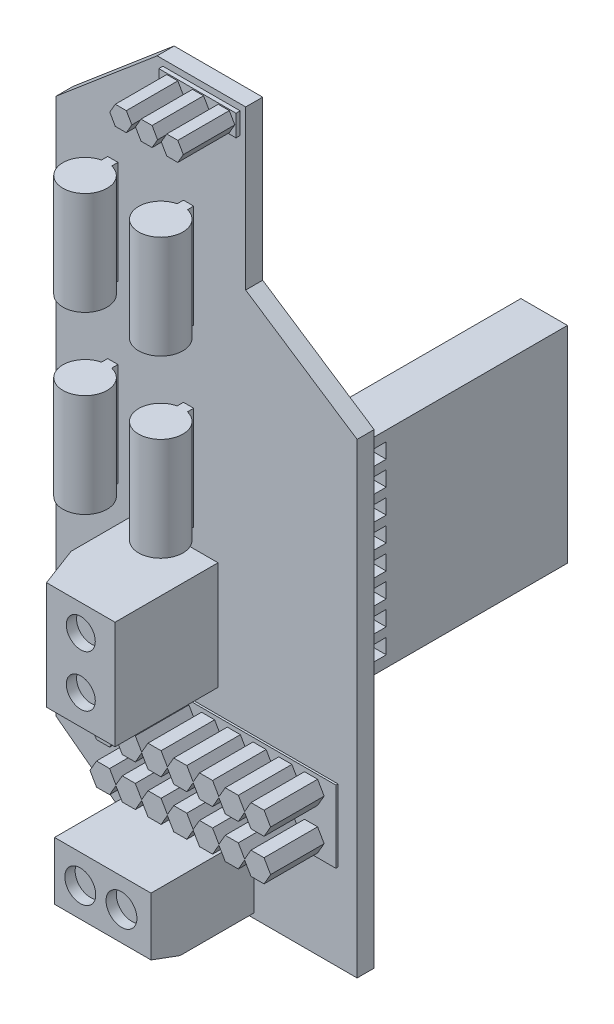
SolidWorks part; units mm, degrees
material "CA"
ref_plane "Plan de face" through (0, 0, 0) normal (0, 0, 1) x (1, 0, 0)
ref_plane "Plan de dessus" through (0, 0, 0) normal (0, 1, 0) x (1, 0, 0)
ref_plane "Plan de droite" through (0, 0, 0) normal (1, 0, 0) x (0, 0, -1)
sketch "Esquisse1" plane through (0, 0, 0) normal (0, 0, 1) x (1, 0, 0)
  line L0 (-11.323, 33.4799) -> (-2.723, 33.4799)
  line L1 (-2.723, 33.4799) -> (-2.723, 18.0799)
  line L2 (-2.723, 18.0799) -> (8.097, 10.9292)
  line L3 (8.097, 10.9292) -> (8.097, -34.3701)
  line L4 (8.097, -34.3701) -> (-11.323, -34.3701)
  line L5 (-11.323, -34.3701) -> (-21.143, -26.9701)
  line L6 (-21.143, -26.9701) -> (-21.143, 25.1718)
  line L7 (-21.143, 25.1718) -> (-11.323, 33.4799)
  dimension "D1" = 67.85
  dimension "D2" = 29.24
  dimension "D3" = 8.6
  dimension "D4" = 18.42
  dimension "D5" = 15.4
  dimension "D6" = 7.4
extrude "Boss.-Extru.1" add sketch "Esquisse1" along normal blind 1.65
sketch "Esquisse2" plane through (0, 0, 1.65) normal (0, 0, 1) x (1, 0, 0)
  line L0 (-15.6256, 15.1125) -> (-15.6256, -11.4034) construction
  line L1 (-10.7643, 32.8838) -> (-3.2638, 32.8838)
  line L2 (-10.7643, 32.8838) -> (-10.7643, 30.8058)
  line L3 (-10.7643, 30.8058) -> (-3.2638, 30.8058)
  line L4 (-3.2638, 32.8838) -> (-3.2638, 30.8058)
  line L5 (-10.7643, 32.8838) -> (-3.2638, 30.8058) construction
  line L6 (-10.7643, 30.8058) -> (-3.2638, 32.8838) construction
  line L7 (-8.2696, 18.1286) -> (-8.2696, -8.3873) construction
  line L9 (-17.8756, 22.6159) -> (-13.3756, 22.6159)
  line L10 (-17.8756, 22.6159) -> (-17.8756, 12.6159)
  line L11 (-17.8756, 12.6159) -> (-13.3756, 12.6159)
  line L12 (-13.3756, 22.6159) -> (-13.3756, 12.6159)
  line L13 (-17.8756, 22.6159) -> (-13.3756, 12.6159) construction
  line L14 (-17.8756, 12.6159) -> (-13.3756, 22.6159) construction
  line L15 (-10.5196, 22.6159) -> (-6.0196, 22.6159)
  line L16 (-10.5196, 22.6159) -> (-10.5196, 12.6159)
  line L17 (-10.5196, 12.6159) -> (-6.0196, 12.6159)
  line L18 (-6.0196, 22.6159) -> (-6.0196, 12.6159)
  line L19 (-10.5196, 22.6159) -> (-6.0196, 12.6159) construction
  line L20 (-10.5196, 12.6159) -> (-6.0196, 22.6159) construction
  line L21 (-17.8756, 5.6159) -> (-13.3756, 5.6159)
  line L22 (-17.8756, 5.6159) -> (-17.8756, -4.3841)
  line L23 (-17.8756, -4.3841) -> (-13.3756, -4.3841)
  line L24 (-13.3756, 5.6159) -> (-13.3756, -4.3841)
  line L25 (-17.8756, 5.6159) -> (-13.3756, -4.3841) construction
  line L26 (-17.8756, -4.3841) -> (-13.3756, 5.6159) construction
  line L27 (-10.5196, 5.6159) -> (-6.0196, 5.6159)
  line L28 (-10.5196, 5.6159) -> (-10.5196, -4.3841)
  line L29 (-10.5196, -4.3841) -> (-6.0196, -4.3841)
  line L30 (-6.0196, 5.6159) -> (-6.0196, -4.3841)
  line L31 (-10.5196, 5.6159) -> (-6.0196, -4.3841) construction
  line L32 (-10.5196, -4.3841) -> (-6.0196, 5.6159) construction
  line L33 (-12.7638, -18.9755) -> (6.2362, -18.9755)
  line L34 (-12.7638, -18.9755) -> (-12.7638, -25.9755)
  line L35 (-12.7638, -25.9755) -> (6.2362, -25.9755)
  line L36 (6.2362, -18.9755) -> (6.2362, -25.9755)
  line L37 (-12.7638, -18.9755) -> (6.2362, -25.9755) construction
  line L38 (-12.7638, -25.9755) -> (6.2362, -18.9755) construction
  point P0 (-7.0141, 31.8448)
  point P9 (-15.6256, 17.6159)
  point P14 (-8.2696, 17.6159)
  point P19 (-15.6256, 0.6159)
  point P24 (-8.2696, 0.6159)
  point P30 (-3.2638, -22.4755)
  dimension "D1" = 4.5
  dimension "D2" = 10
  dimension "D3" = 7
  dimension "D4" = 7
  dimension "D5" = 19
  dimension "D6" = 7
extrude "Boss.-Extru.2" add sketch "Esquisse2" along normal blind 5.4
sketch "Esquisse3" plane through (0, 0, 1.65) normal (0, 0, 1) x (1, 0, 0)
  line L5 (-11.2863, -33.9075) -> (-1.9184, -33.9075)
  line L6 (-11.2863, -33.9075) -> (-11.2863, -27.2388)
  line L7 (-11.2863, -27.2388) -> (-1.9184, -27.2388)
  line L8 (-1.9184, -33.9075) -> (-1.9184, -27.2388)
  line L9 (-11.2863, -33.9075) -> (-1.9184, -27.2388) construction
  line L10 (-11.2863, -27.2388) -> (-1.9184, -33.9075) construction
  line L11 (-5.4116, -16.6801) -> (-13.5092, -16.6801)
  line L12 (-5.4116, -16.6801) -> (-5.4116, -6.2008)
  line L13 (-5.4116, -6.2008) -> (-13.5092, -6.2008)
  line L14 (-13.5092, -16.6801) -> (-13.5092, -6.2008)
  line L15 (-5.4116, -16.6801) -> (-13.5092, -6.2008) construction
  line L16 (-5.4116, -6.2008) -> (-13.5092, -16.6801) construction
  point P0 (-6.6024, -30.5731)
  point P5 (-9.4604, -11.4404)
extrude "Boss.-Extru.3" add sketch "Esquisse3" along normal blind 10
sketch "Esquisse4" plane through (0, 0, 0) normal (0, 0, -1) x (-1, 0, 0)
  line L0 (-8.097, -34.3701) -> (-8.097, 10.9292) construction
  line L1 (-5.277, 7.4799) -> (-0.757, 7.4799)
  line L2 (-5.277, 7.4799) -> (-5.277, -12.5201)
  line L3 (-5.277, -12.5201) -> (-0.757, -12.5201)
  line L4 (-0.757, 7.4799) -> (-0.757, -12.5201)
  line L5 (-5.277, 7.4799) -> (-0.757, -12.5201) construction
  line L6 (-5.277, -12.5201) -> (-0.757, 7.4799) construction
  line L7 (2.723, 33.4799) -> (11.323, 33.4799) construction
  point P0 (-3.017, -2.5201)
  dimension "D1" = 7.34
  dimension "D2" = 4.52
  dimension "D3" = 20
  dimension "D4" = 26
extrude "Boss.-Extru.4" add sketch "Esquisse4" along normal blind 21.6
sketch "Esquisse5" plane through (0, -4.3841, 0) normal (0, -1, 0) x (1, 0, 0)
  line L0 (-13.3756, 7.05) -> (-17.8756, 1.65) construction
  line L10 (-17.8756, 1.65) -> (-13.3756, 1.65) construction
  line L11 (-16.1256, 2.75) -> (-15.1256, 2.75)
  line L12 (-16.1256, 2.75) -> (-16.1256, 1.65)
  line L13 (-16.1256, 1.65) -> (-15.1256, 1.65)
  line L14 (-15.1256, 2.75) -> (-15.1256, 1.65)
  line L15 (-16.1256, 2.75) -> (-15.1256, 1.65) construction
  line L16 (-16.1256, 1.65) -> (-15.1256, 2.75) construction
  circle A2 centre (-15.6256, 4.35) radius 2.15
  point P7 (-15.6256, 2.2)
  line M2 (-17.8756, 1.65) -> (-13.3756, 1.65)
  line M3 (-13.3756, 1.65) -> (-13.3756, 7.05)
  line M4 (-13.3756, 7.05) -> (-17.8756, 7.05)
  line M5 (-17.8756, 7.05) -> (-17.8756, 1.65)
  dimension "D1" = 4.3
  dimension "D2" = 1
extrude "Enlèv. mat.-Extru.3" cut sketch "Esquisse5" against normal blind 27 contours A2 L14 L12 M2 M3 M4 M5
sketch "Esquisse6" plane through (0, 22.6159, 0) normal (0, 1, 0) x (1, 0, 0)
  line L0 (-6.0196, -7.05) -> (-10.5196, -1.65) construction
  line L1 (-6.0196, -1.65) -> (-10.5196, -1.65) construction
  line L2 (-7.7696, -2.75) -> (-8.7696, -2.75)
  line L3 (-7.7696, -2.75) -> (-7.7696, -1.65)
  line L4 (-7.7696, -1.65) -> (-8.7696, -1.65)
  line L5 (-8.7696, -2.75) -> (-8.7696, -1.65)
  line L6 (-7.7696, -2.75) -> (-8.7696, -1.65) construction
  line L7 (-7.7696, -1.65) -> (-8.7696, -2.75) construction
  circle A0 centre (-8.2696, -4.35) radius 2.15
  point P6 (-8.2696, -2.2)
  line M2 (-6.0196, -1.65) -> (-10.5196, -1.65)
  line M3 (-10.5196, -1.65) -> (-10.5196, -7.05)
  line M4 (-10.5196, -7.05) -> (-6.0196, -7.05)
  line M5 (-6.0196, -7.05) -> (-6.0196, -1.65)
  dimension "D1" = 4.3
  dimension "D2" = 1
extrude "Enlèv. mat.-Extru.4" cut sketch "Esquisse6" against normal blind 27 contours A0 L5 L3 M2 M3 M4 M5
sketch "Esquisse8" plane through (0, 0, 7.05) normal (0, 0, 1) x (1, 0, 0)
  line L0 (6.2362, -18.9755) -> (-12.7638, -18.9755) construction
  line L1 (-10.5397, -19.3723) -> (-11.8109, -19.3723)
  line L2 (-11.8109, -19.3723) -> (-12.4465, -20.4732)
  line L3 (-12.4465, -20.4732) -> (-11.8109, -21.5742)
  line L4 (-11.8109, -21.5742) -> (-10.5397, -21.5742)
  line L5 (-10.5397, -21.5742) -> (-9.9041, -20.4732)
  line L6 (-9.9041, -20.4732) -> (-10.5397, -19.3723)
  line L7 (-8.0397, -19.3723) -> (-9.3109, -19.3723)
  line L8 (-9.3109, -19.3723) -> (-9.9465, -20.4732)
  line L9 (-9.9465, -20.4732) -> (-9.3109, -21.5742)
  line L10 (-9.3109, -21.5742) -> (-8.0397, -21.5742)
  line L11 (-8.0397, -21.5742) -> (-7.4041, -20.4732)
  line L12 (-7.4041, -20.4732) -> (-8.0397, -19.3723)
  line L13 (-5.5397, -19.3723) -> (-6.8109, -19.3723)
  line L14 (-6.8109, -19.3723) -> (-7.4465, -20.4732)
  line L15 (-7.4465, -20.4732) -> (-6.8109, -21.5742)
  line L16 (-6.8109, -21.5742) -> (-5.5397, -21.5742)
  line L17 (-5.5397, -21.5742) -> (-4.9041, -20.4732)
  line L18 (-4.9041, -20.4732) -> (-5.5397, -19.3723)
  line L19 (-3.0397, -19.3723) -> (-4.3109, -19.3723)
  line L20 (-4.3109, -19.3723) -> (-4.9465, -20.4732)
  line L21 (-4.9465, -20.4732) -> (-4.3109, -21.5742)
  line L22 (-4.3109, -21.5742) -> (-3.0397, -21.5742)
  line L23 (-3.0397, -21.5742) -> (-2.4041, -20.4732)
  line L24 (-2.4041, -20.4732) -> (-3.0397, -19.3723)
  line L25 (-0.5397, -19.3723) -> (-1.8109, -19.3723)
  line L26 (-1.8109, -19.3723) -> (-2.4465, -20.4732)
  line L27 (-2.4465, -20.4732) -> (-1.8109, -21.5742)
  line L28 (-1.8109, -21.5742) -> (-0.5397, -21.5742)
  line L29 (-0.5397, -21.5742) -> (0.0959, -20.4732)
  line L30 (0.0959, -20.4732) -> (-0.5397, -19.3723)
  line L31 (1.9603, -19.3723) -> (0.6891, -19.3723)
  line L32 (0.6891, -19.3723) -> (0.0535, -20.4732)
  line L33 (0.0535, -20.4732) -> (0.6891, -21.5742)
  line L34 (0.6891, -21.5742) -> (1.9603, -21.5742)
  line L35 (1.9603, -21.5742) -> (2.5959, -20.4732)
  line L36 (2.5959, -20.4732) -> (1.9603, -19.3723)
  line L37 (4.4603, -19.3723) -> (3.1891, -19.3723)
  line L38 (3.1891, -19.3723) -> (2.5535, -20.4732)
  line L39 (2.5535, -20.4732) -> (3.1891, -21.5742)
  line L40 (3.1891, -21.5742) -> (4.4603, -21.5742)
  line L41 (4.4603, -21.5742) -> (5.0959, -20.4732)
  line L42 (5.0959, -20.4732) -> (4.4603, -19.3723)
  line L43 (-8.0397, -23.3723) -> (-9.3109, -23.3723)
  line L44 (-9.3109, -23.3723) -> (-9.9465, -24.4732)
  line L45 (-9.9465, -24.4732) -> (-9.3109, -25.5742)
  line L46 (-9.3109, -25.5742) -> (-8.0397, -25.5742)
  line L47 (-8.0397, -25.5742) -> (-7.4041, -24.4732)
  line L48 (-7.4041, -24.4732) -> (-8.0397, -23.3723)
  line L49 (-5.5397, -23.3723) -> (-6.8109, -23.3723)
  line L50 (-6.8109, -23.3723) -> (-7.4465, -24.4732)
  line L51 (-7.4465, -24.4732) -> (-6.8109, -25.5742)
  line L52 (-6.8109, -25.5742) -> (-5.5397, -25.5742)
  line L53 (-5.5397, -25.5742) -> (-4.9041, -24.4732)
  line L54 (-4.9041, -24.4732) -> (-5.5397, -23.3723)
  line L55 (-3.0397, -23.3723) -> (-4.3109, -23.3723)
  line L56 (-4.3109, -23.3723) -> (-4.9465, -24.4732)
  line L57 (-4.9465, -24.4732) -> (-4.3109, -25.5742)
  line L58 (-4.3109, -25.5742) -> (-3.0397, -25.5742)
  line L59 (-3.0397, -25.5742) -> (-2.4041, -24.4732)
  line L60 (-2.4041, -24.4732) -> (-3.0397, -23.3723)
  line L61 (-0.5397, -23.3723) -> (-1.8109, -23.3723)
  line L62 (-1.8109, -23.3723) -> (-2.4465, -24.4732)
  line L63 (-2.4465, -24.4732) -> (-1.8109, -25.5742)
  line L64 (-1.8109, -25.5742) -> (-0.5397, -25.5742)
  line L65 (-0.5397, -25.5742) -> (0.0959, -24.4732)
  line L66 (0.0959, -24.4732) -> (-0.5397, -23.3723)
  line L67 (1.9603, -23.3723) -> (0.6891, -23.3723)
  line L68 (0.6891, -23.3723) -> (0.0535, -24.4732)
  line L69 (0.0535, -24.4732) -> (0.6891, -25.5742)
  line L70 (0.6891, -25.5742) -> (1.9603, -25.5742)
  line L71 (1.9603, -25.5742) -> (2.5959, -24.4732)
  line L72 (2.5959, -24.4732) -> (1.9603, -23.3723)
  line L73 (4.4603, -23.3723) -> (3.1891, -23.3723)
  line L74 (3.1891, -23.3723) -> (2.5535, -24.4732)
  line L75 (2.5535, -24.4732) -> (3.1891, -25.5742)
  line L76 (3.1891, -25.5742) -> (4.4603, -25.5742)
  line L77 (4.4603, -25.5742) -> (5.0959, -24.4732)
  line L78 (5.0959, -24.4732) -> (4.4603, -23.3723)
  line L79 (-10.5397, -23.3723) -> (-11.8109, -23.3723)
  line L80 (-11.8109, -23.3723) -> (-12.4465, -24.4732)
  line L81 (-12.4465, -24.4732) -> (-11.8109, -25.5742)
  line L82 (-11.8109, -25.5742) -> (-10.5397, -25.5742)
  line L83 (-10.5397, -25.5742) -> (-9.9041, -24.4732)
  line L84 (-9.9041, -24.4732) -> (-10.5397, -23.3723)
  circle A0 centre (-11.1753, -20.4732) radius 1.1009 construction
  circle A1 centre (-8.6753, -20.4732) radius 1.1009 construction
  circle A2 centre (-6.1753, -20.4732) radius 1.1009 construction
  circle A3 centre (-3.6753, -20.4732) radius 1.1009 construction
  circle A4 centre (-1.1753, -20.4732) radius 1.1009 construction
  circle A5 centre (1.3247, -20.4732) radius 1.1009 construction
  circle A6 centre (3.8247, -20.4732) radius 1.1009 construction
  circle A7 centre (-8.6753, -24.4732) radius 1.1009 construction
  circle A8 centre (-6.1753, -24.4732) radius 1.1009 construction
  circle A9 centre (-3.6753, -24.4732) radius 1.1009 construction
  circle A10 centre (-1.1753, -24.4732) radius 1.1009 construction
  circle A11 centre (1.3247, -24.4732) radius 1.1009 construction
  circle A12 centre (3.8247, -24.4732) radius 1.1009 construction
  circle A13 centre (-11.1753, -24.4732) radius 1.1009 construction
  line M2 (6.2362, -25.9755) -> (6.2362, -18.9755)
  line M3 (6.2362, -18.9755) -> (-12.7638, -18.9755)
  line M4 (-12.7638, -18.9755) -> (-12.7638, -25.9755)
  line M5 (-12.7638, -25.9755) -> (6.2362, -25.9755)
  dimension "D1" = 7
  dimension "D2" = 2
extrude "Enlèv. mat.-Extru.10" cut sketch "Esquisse8" against normal blind 5.2 contours L84 L44 L43 L48 L50 L49 L54 L56 L55 L60 L62 L61 L66 L68 L67 L72 L74 L73 L78 L77 L76 L75 L71 L70 L69 L65 L64 L63 L59 L58 L57 L53 L52 L51 L47 L46 L45 L83 L82 L81 L80 L79 L42 L41 L40 M5 M2 M3 M4
sketch "Esquisse9" plane through (-13.5092, 0, 0) normal (-1, 0, 0) x (0, 0, 1)
  line L0 (1.65, -9.2008) -> (11.65, -9.2008) construction
  line L1 (1.65, -6.2008) -> (1.65, -16.6801) construction
  line L2 (11.65, -6.2008) -> (11.65, -16.6801) construction
  line L3 (1.65, -13.2008) -> (11.65, -13.2008) construction
  line L4 (11.65, -6.2008) -> (1.65, -6.2008) construction
  line L6 (2.4565, -7.4967) -> (7.1773, -7.4967)
  line L7 (2.4565, -7.4967) -> (2.4565, -10.9048)
  line L8 (2.4565, -10.9048) -> (7.1773, -10.9048)
  line L9 (7.1773, -7.4967) -> (7.1773, -10.9048)
  line L10 (2.4565, -7.4967) -> (7.1773, -10.9048) construction
  line L11 (2.4565, -10.9048) -> (7.1773, -7.4967) construction
  line L12 (2.4565, -11.4967) -> (7.1773, -11.4967)
  line L13 (2.4565, -11.4967) -> (2.4565, -14.9048)
  line L14 (2.4565, -14.9048) -> (7.1773, -14.9048)
  line L15 (7.1773, -11.4967) -> (7.1773, -14.9048)
  line L16 (2.4565, -11.4967) -> (7.1773, -14.9048) construction
  line L17 (2.4565, -14.9048) -> (7.1773, -11.4967) construction
  point P10 (4.8169, -9.2008)
  point P15 (4.8169, -13.2008)
  dimension "D1" = 4
  dimension "D2" = 3
extrude "Enlèv. mat.-Extru.11" cut sketch "Esquisse9" against normal blind 5.2
sketch "Esquisse10" plane through (0, -16.6801, 0) normal (0, -1, 0) x (1, 0, 0)
  line L0 (-13.5092, 11.65) -> (-13.5092, 7.8248)
  line L1 (-13.5092, 11.65) -> (-13.5092, 1.65) construction
  line L2 (-13.5092, 7.8248) -> (-12.0645, 11.65)
  line L3 (-13.5092, 11.65) -> (-5.4116, 11.65) construction
  line L4 (-12.0645, 11.65) -> (-13.5092, 11.65)
extrude "Enlèv. mat.-Extru.12" cut sketch "Esquisse10" against normal up to surface (10.4793 mm away) up to face at (-9.4604, -6.2008, 6.65)
sketch "Esquisse11" plane through (0, 0, 11.65) normal (0, 0, 1) x (1, 0, 0)
  line L0 (-8.738, -6.2008) -> (-8.738, -16.6801) construction
  line L1 (-5.4116, -6.2008) -> (-12.0645, -6.2008) construction
  line L2 (-12.0645, -16.6801) -> (-5.4116, -16.6801) construction
  circle A0 centre (-8.738, -8.7833) radius 1.4089
  circle A1 centre (-8.738, -13.7833) radius 1.4089
  dimension "D1" = 5
extrude "Enlèv. mat.-Extru.13" cut sketch "Esquisse11" against normal blind 1
sketch "Esquisse12" plane through (5.277, 0, 0) normal (1, 0, 0) x (0, 0, -1)
  line L0 (0, 33.4799) -> (0, 25.1718) construction
  line L1 (0, -11.4237) -> (4, -11.4237)
  line L2 (0, -11.4237) -> (0, -9.9502)
  line L3 (0, -9.9502) -> (4, -9.9502)
  line L4 (4, -11.4237) -> (4, -9.9502)
  line L5 (0, -11.4237) -> (4, -9.9502) construction
  line L6 (0, -9.9502) -> (4, -11.4237) construction
  point P0 (2, -10.6869)
  dimension "D1" = 4
extrude "Enlèv. mat.-Extru.14" cut sketch "Esquisse12" against normal blind 5
pattern_linear "Répétition linéaire2" count 8 spacing 2.35 along (0, 1, 0) of "Enlèv. mat.-Extru.14"
sketch "Esquisse13" plane through (0, 0, 7.05) normal (0, 0, 1) x (1, 0, 0)
  line L0 (-3.2638, 32.8838) -> (-10.7643, 32.8838) construction
  line L1 (-8.9145, 30.9154) -> (-8.378, 31.8448)
  line L2 (-8.378, 31.8448) -> (-8.9145, 32.7741)
  line L3 (-8.9145, 32.7741) -> (-9.9877, 32.7741)
  line L4 (-9.9877, 32.7741) -> (-10.5243, 31.8448)
  line L5 (-10.5243, 31.8448) -> (-9.9877, 30.9154)
  line L6 (-9.9877, 30.9154) -> (-8.9145, 30.9154)
  line L7 (-10.7643, 31.8448) -> (-3.2638, 31.8448) construction
  line L8 (-10.7643, 32.8838) -> (-10.7643, 30.8058) construction
  line L9 (-3.2638, 30.8058) -> (-3.2638, 32.8838) construction
  line L10 (-6.4145, 30.9154) -> (-5.878, 31.8448)
  line L11 (-5.878, 31.8448) -> (-6.4145, 32.7741)
  line L12 (-6.4145, 32.7741) -> (-7.4877, 32.7741)
  line L13 (-7.4877, 32.7741) -> (-8.0243, 31.8448)
  line L14 (-8.0243, 31.8448) -> (-7.4877, 30.9154)
  line L15 (-7.4877, 30.9154) -> (-6.4145, 30.9154)
  line L16 (-3.9145, 30.9154) -> (-3.378, 31.8448)
  line L17 (-3.378, 31.8448) -> (-3.9145, 32.7741)
  line L18 (-3.9145, 32.7741) -> (-4.9877, 32.7741)
  line L19 (-4.9877, 32.7741) -> (-5.5243, 31.8448)
  line L20 (-5.5243, 31.8448) -> (-4.9877, 30.9154)
  line L21 (-4.9877, 30.9154) -> (-3.9145, 30.9154)
  circle A0 centre (-9.4511, 31.8448) radius 0.9294 construction
  circle A1 centre (-6.9511, 31.8448) radius 0.9294 construction
  circle A2 centre (-4.4511, 31.8448) radius 0.9294 construction
  line M2 (-3.2638, 30.8058) -> (-3.2638, 32.8838)
  line M3 (-3.2638, 32.8838) -> (-10.7643, 32.8838)
  line M4 (-10.7643, 32.8838) -> (-10.7643, 30.8058)
  line M5 (-10.7643, 30.8058) -> (-3.2638, 30.8058)
  dimension "D1" = 3
extrude "Enlèv. mat.-Extru.15" cut sketch "Esquisse13" against normal blind 5 contours L21 L20 L19 L18 L17 L16 L15 L14 L13 L12 L11 L10 L6 L5 L4 L3 L2 L1 M5 M2 M3 M4
sketch "Esquisse14" plane through (0, -33.9075, 0) normal (0, -1, 0) x (1, 0, 0)
  line L0 (-8.7863, 1.65) -> (-8.7863, 11.65) construction
  line L1 (-11.2863, 1.65) -> (-1.9184, 1.65) construction
  line L2 (-11.2863, 11.65) -> (-1.9184, 11.65) construction
  line L3 (-4.7863, 1.65) -> (-4.7863, 11.65) construction
  line L4 (-11.2863, 11.65) -> (-11.2863, 1.65) construction
  line L5 (-10.422, 3.293) -> (-7.1507, 3.293)
  line L6 (-10.422, 3.293) -> (-10.422, 7.3531)
  line L7 (-10.422, 7.3531) -> (-7.1507, 7.3531)
  line L8 (-7.1507, 3.293) -> (-7.1507, 7.3531)
  line L9 (-10.422, 3.293) -> (-7.1507, 7.3531) construction
  line L10 (-10.422, 7.3531) -> (-7.1507, 3.293) construction
  line L11 (-6.422, 3.293) -> (-3.1507, 3.293)
  line L12 (-6.422, 3.293) -> (-6.422, 7.3531)
  line L13 (-6.422, 7.3531) -> (-3.1507, 7.3531)
  line L14 (-3.1507, 3.293) -> (-3.1507, 7.3531)
  line L15 (-6.422, 3.293) -> (-3.1507, 7.3531) construction
  line L16 (-6.422, 7.3531) -> (-3.1507, 3.293) construction
  point P8 (-8.7863, 5.323)
  point P13 (-4.7863, 5.323)
  dimension "D1" = 4
  dimension "D2" = 2.5
extrude "Enlèv. mat.-Extru.16" cut sketch "Esquisse14" against normal blind 4
sketch "Esquisse15" plane through (-11.2863, 0, 0) normal (-1, 0, 0) x (0, 0, 1)
  line L0 (11.65, -33.9075) -> (8.8274, -33.9075)
  line L1 (11.65, -33.9075) -> (1.65, -33.9075) construction
  line L2 (8.8274, -33.9075) -> (11.65, -32.8629)
  line L3 (11.65, -27.2388) -> (11.65, -33.9075) construction
  line L4 (11.65, -32.8629) -> (11.65, -33.9075)
extrude "Enlèv. mat.-Extru.17" cut sketch "Esquisse15" against normal up to surface (9.3679 mm away) up to face at (-1.9184, -30.5731, 6.65)
sketch "Esquisse16" plane through (0, 0, 11.65) normal (0, 0, 1) x (1, 0, 0)
  line L0 (-11.2863, -30.0509) -> (-1.9184, -30.0509) construction
  line L1 (-11.2863, -27.2388) -> (-11.2863, -32.8629) construction
  line L2 (-1.9184, -32.8629) -> (-1.9184, -27.2388) construction
  circle A0 centre (-8.7863, -30.0509) radius 1.5
  circle A1 centre (-4.7863, -30.0509) radius 1.5
  dimension "D1" = 3
  dimension "D2" = 4
  dimension "D3" = 2.5
extrude "Enlèv. mat.-Extru.18" cut sketch "Esquisse16" against normal blind 1
sketch "Esquisse17" plane through (0, 0, 2.4565) normal (0, 0, 1) x (1, 0, 0)
  line L1 (-12.5513, -10.458) -> (-8.6662, -10.458)
  line L2 (-12.5513, -10.458) -> (-12.5513, -7.7266)
  line L3 (-12.5513, -7.7266) -> (-8.6662, -7.7266)
  line L4 (-8.6662, -10.458) -> (-8.6662, -7.7266)
  line L5 (-12.5513, -10.458) -> (-8.6662, -7.7266) construction
  line L6 (-12.5513, -7.7266) -> (-8.6662, -10.458) construction
  line L7 (-12.5513, -14.5867) -> (-8.6662, -14.5867)
  line L8 (-12.5513, -14.5867) -> (-12.5513, -11.8553)
  line L9 (-12.5513, -11.8553) -> (-8.6662, -11.8553)
  line L10 (-8.6662, -14.5867) -> (-8.6662, -11.8553)
  line L11 (-12.5513, -14.5867) -> (-8.6662, -11.8553) construction
  line L12 (-12.5513, -11.8553) -> (-8.6662, -14.5867) construction
  point P0 (-10.6087, -9.0923)
  point P5 (-10.6087, -13.221)
extrude "Boss.-Extru.5" add sketch "Esquisse17" along normal blind 4
sketch "Esquisse18" plane through (-12.5513, 0, 0) normal (-1, 0, 0) x (0, 0, 1)
  line L1 (3.9827, -7.8582) -> (4.9036, -7.8582)
  line L2 (3.9827, -7.8582) -> (3.9827, -10.1483)
  line L3 (3.9827, -10.1483) -> (4.9036, -10.1483)
  line L4 (4.9036, -7.8582) -> (4.9036, -10.1483)
  line L5 (3.9827, -7.8582) -> (4.9036, -10.1483) construction
  line L6 (3.9827, -10.1483) -> (4.9036, -7.8582) construction
  line L7 (3.9827, -12.1329) -> (4.9036, -12.1329)
  line L8 (3.9827, -12.1329) -> (3.9827, -14.2934)
  line L9 (3.9827, -14.2934) -> (4.9036, -14.2934)
  line L10 (4.9036, -12.1329) -> (4.9036, -14.2934)
  line L11 (3.9827, -12.1329) -> (4.9036, -14.2934) construction
  line L12 (3.9827, -14.2934) -> (4.9036, -12.1329) construction
  point P0 (4.4432, -9.0033)
  point P5 (4.4432, -13.2131)
extrude "Enlèv. mat.-Extru.19" cut sketch "Esquisse18" against normal blind 2
